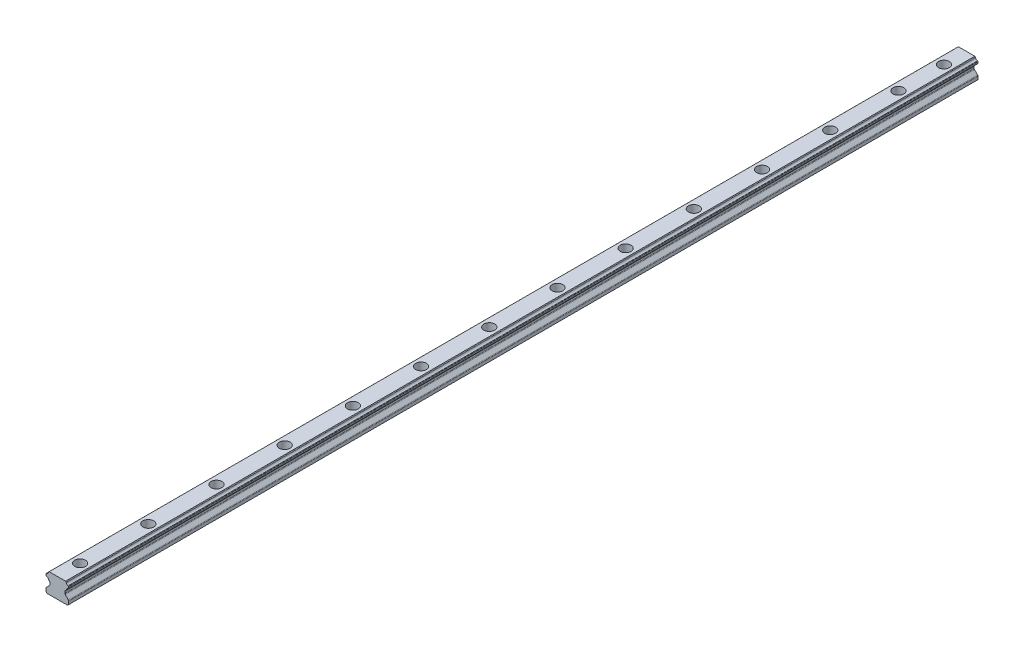
SolidWorks part; units mm, degrees
material "Stainless Steel (ferritic)"
ref_plane "Front Plane" through (0, 0, 0) normal (0, 0, 1) x (1, 0, 0)
ref_plane "Top Plane" through (0, 0, 0) normal (0, 1, 0) x (1, 0, 0)
ref_plane "Right Plane" through (0, 0, 0) normal (1, 0, 0) x (0, 0, -1)
sketch "Sketch10" plane through (0, 0, 0) normal (0, 0, 1) x (1, 0, 0)
  line L0 (-10, -10.3385) -> (-10, -13)
  line L1 (-10, -13) -> (-9, -14)
  line L2 (-9, -14) -> (9, -14)
  line L3 (6.8929, -6.8172) -> (9.7071, -9.6314)
  line L4 (6.6, -4.5499) -> (6.6, -6.1101)
  line L5 (7.6302, -3.1056) -> (6.8929, -3.8428)
  line L6 (9.8536, -0.8822) -> (9.6906, -1.0451)
  line L7 (10, 0.5286) -> (10, -0.5286)
  line L8 (9.6906, 1.0451) -> (9.8536, 0.8822)
  line L9 (7.2357, 3.5) -> (7.6325, 3.1032)
  line L10 (10, -13) -> (9, -14)
  line L11 (10, -10.3385) -> (10, -13)
  line L12 (7.2357, 3.5) -> (-7.2357, 3.5)
  line L13 (-7.2357, 3.5) -> (-7.6325, 3.1032)
  line L14 (-9.6906, 1.0451) -> (-9.8536, 0.8822)
  line L15 (-10, 0.5286) -> (-10, -0.5286)
  line L16 (-9.8536, -0.8822) -> (-9.6906, -1.0451)
  line L17 (-7.6302, -3.1056) -> (-6.8929, -3.8428)
  line L18 (-6.6, -4.5499) -> (-6.6, -6.1101)
  line L19 (-6.8929, -6.8172) -> (-9.7071, -9.6314)
  line L20 (0, -14) -> (0, 3.5) construction
  line L21 (-10, 0) -> (0, 0) construction
  arc A0 (-9.7071, -9.6314) -> (-10, -10.3385) centre (-9, -10.3385) ccw
  arc A1 (6.8929, -6.8172) -> (6.6, -6.1101) centre (7.6, -6.1101) cw
  arc A2 (6.6, -4.5499) -> (6.8929, -3.8428) centre (7.6, -4.5499) cw
  arc A3 (7.8468, -2.7675) -> (7.6302, -3.1056) centre (7.3529, -2.6895) cw
  arc A4 (7.8468, -2.7675) -> (9.4318, -1.1825) centre (9.8106, -3.1463) cw
  arc A5 (9.6906, -1.0451) -> (9.4318, -1.1825) centre (9.3371, -0.6915) cw
  arc A6 (10, -0.5286) -> (9.8536, -0.8822) centre (9.5, -0.5286) cw
  arc A7 (9.8536, 0.8822) -> (10, 0.5286) centre (9.5, 0.5286) cw
  arc A8 (9.4224, 1.1941) -> (9.6906, 1.0451) centre (9.3254, 0.7036) cw
  arc A9 (9.4224, 1.1941) -> (7.8482, 2.768) centre (9.8101, 3.1561) cw
  arc A10 (7.6325, 3.1032) -> (7.8482, 2.768) centre (7.3547, 2.6875) cw
  arc A11 (9.7071, -9.6314) -> (10, -10.3385) centre (9, -10.3385) cw
  arc A12 (-7.6325, 3.1032) -> (-7.8482, 2.768) centre (-7.3547, 2.6875) ccw
  arc A13 (-9.4224, 1.1941) -> (-7.8482, 2.768) centre (-9.8101, 3.1561) ccw
  arc A14 (-9.4224, 1.1941) -> (-9.6906, 1.0451) centre (-9.3254, 0.7036) ccw
  arc A15 (-9.8536, 0.8822) -> (-10, 0.5286) centre (-9.5, 0.5286) ccw
  arc A16 (-10, -0.5286) -> (-9.8536, -0.8822) centre (-9.5, -0.5286) ccw
  arc A17 (-9.6906, -1.0451) -> (-9.4318, -1.1825) centre (-9.3371, -0.6915) ccw
  arc A18 (-7.8468, -2.7675) -> (-9.4318, -1.1825) centre (-9.8106, -3.1463) ccw
  arc A19 (-7.8468, -2.7675) -> (-7.6302, -3.1056) centre (-7.3529, -2.6895) ccw
  arc A20 (-6.6, -4.5499) -> (-6.8929, -3.8428) centre (-7.6, -4.5499) ccw
  arc A21 (-6.8929, -6.8172) -> (-6.6, -6.1101) centre (-7.6, -6.1101) ccw
  dimension "D3" = 17.5
  dimension "D4" = 135
  dimension "D1" = 3.5
  dimension "D2" = 1
  dimension "D5" = 14
extrude "BODY" add sketch "Sketch10" along normal mid plane 800
hole_wizard "CBORE for M6 SHCS1" positions "Sketch12" profile "Sketch11" counterbore size "M6" standard "ANSI Metric" end condition through all
sketch "Sketch12" plane through (0, 3.5, 0) normal (0, 1, 0) x (1, 0, 0)
  line L0 (0, -400) -> (0, -380) construction
  line L2 (7.2357, -400) -> (-7.2357, -400) construction
  point P0 (0, -380)
  dimension "D1" = 20
sketch "Sketch11" plane through (0, 3.5, 380) normal (1, 0, 0) x (0, 0, 1)
  line L0 (0, 0) -> (0, 17.5)
  line L1 (0, 17.5) -> (3, 17.5)
  line L3 (3, 17.5) -> (3, 8.4)
  line L4 (3, 8.4) -> (4.75, 8.4)
  line L5 (4.75, 8.4) -> (4.75, 0)
  line L7 (4.75, 0) -> (0, 0)
  line L11 (0, -6.35) -> (0, 107.95) construction
  dimension "Thru Hole Dia." = 6
  dimension "Thru Hole Depth" = 17.5
  dimension "C'Bore Dia." = 9.5
  dimension "C'Bore Depth" = 8.4
mirror "MIRROR FIRST COUNTERBORE" about plane through (0, 0, 0) normal (0, 0, 1) of "CBORE for M6 SHCS1"
sketch "END TO END HOLES" plane through (0, 0, 0) normal (0, 1, 0) x (1, 0, 0)
  line L0 (0, -380) -> (0, 380) construction
pattern_linear "LP CBORE" count 13 spacing 60 along (0, 0, -1) of "CBORE for M6 SHCS1"
sketch "Sketch13" [suppressed] plane through (65.1, 0, 0) normal (1, 0, 0) x (0, 0, -1)
  circle A0 centre (-354.406, -208.0955) radius 3.175 construction
  circle A2 centre (-354.406, -208.0955) radius 3.175
  circle A4 centre (-354.406, 28.006) radius 3.425
  circle A5 centre (-354.406, -208.0955) radius 3.425
  dimension "D1" = 0.25
equation "\"D1@LP CBORE\"    = INT(\"DISTANCE@END TO END HOLES\"/60)+1"
